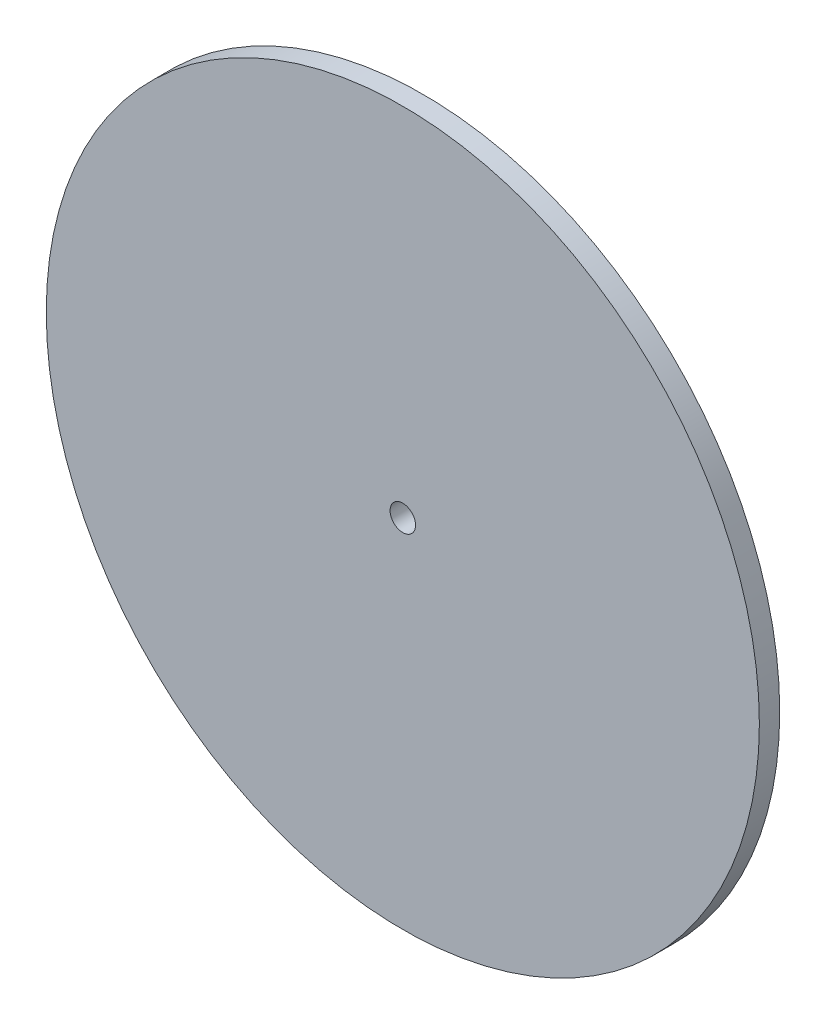
SolidWorks part; units mm, degrees
ref_plane "Plan de face" through (0, 0, 0) normal (0, 0, 1) x (1, 0, 0)
ref_plane "Plan de dessus" through (0, 0, 0) normal (0, 1, 0) x (1, 0, 0)
ref_plane "Plan de droite" through (0, 0, 0) normal (1, 0, 0) x (0, 0, -1)
sketch "Esquisse1" plane through (0, 0, 0) normal (0, 0, 1) x (1, 0, 0)
  circle A0 centre (0, 0) radius 70
  dimension "D1" = 140
extrude "Boss.-Extru.1" add sketch "Esquisse1" along normal blind 4
sketch "Esquisse2" plane through (0, 0, 0) normal (0, 0, -1) x (-1, 0, 0)
  circle A0 centre (0, 0) radius 2.5
  dimension "D1" = 5
extrude "Enlèv. mat.-Extru.1" cut sketch "Esquisse2" against normal through all
